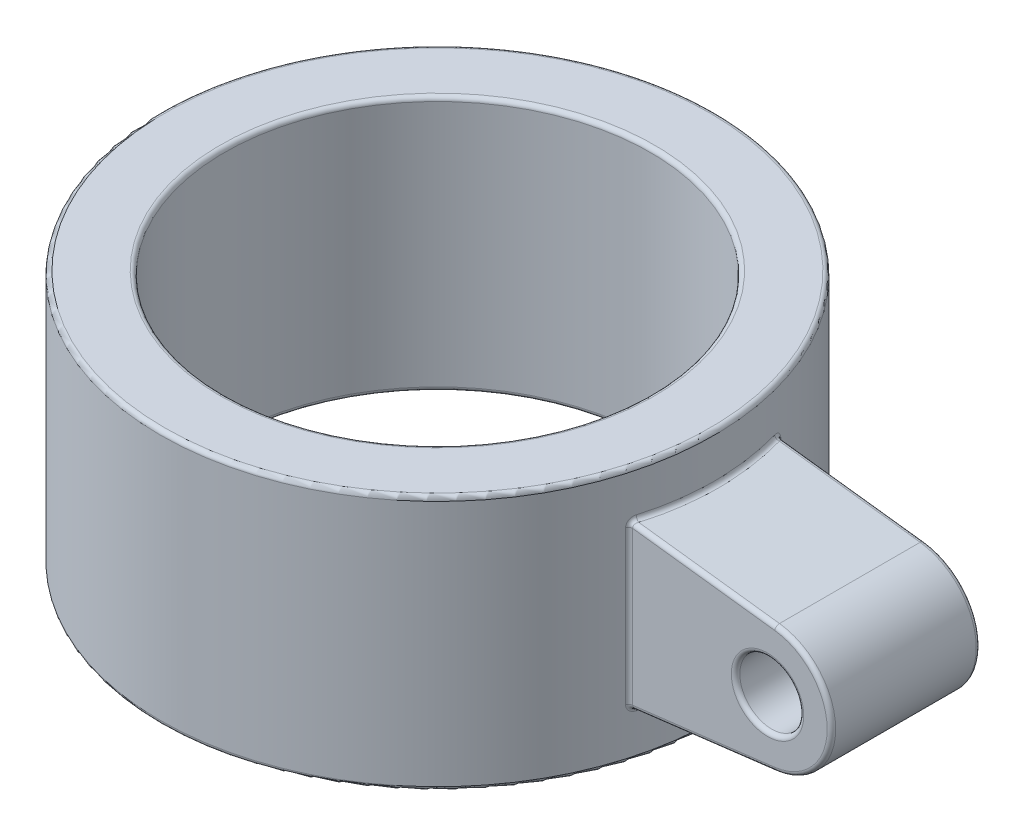
SolidWorks part; units mm, degrees
ref_plane "Front Plane" through (0, 0, 0) normal (0, 0, 1) x (1, 0, 0)
ref_plane "Top Plane" through (0, 0, 0) normal (0, 1, 0) x (1, 0, 0)
ref_plane "Right Plane" through (0, 0, 0) normal (1, 0, 0) x (0, 0, -1)
sketch "Sketch1" plane through (0, 0, 0) normal (0, 1, 0) x (1, 0, 0)
  circle A0 centre (0, 0) radius 5
  circle A1 centre (0, 0) radius 6.5
  dimension "D1" = 10
  dimension "D2" = 1.5
extrude "Boss-Extrude1" add sketch "Sketch1" along normal mid plane 6
sketch "Sketch2" plane through (0, 0, 0) normal (0, 0, 1) x (1, 0, 0)
  line L4 (5.5, 2) -> (5.5, -2)
  line L5 (5.5, -2) -> (9.682, -1.4889)
  line L6 (5.5, 2) -> (9.682, 1.4889)
  arc A0 (9.682, -1.4889) -> (9.682, 1.4889) centre (9.5, 0) ccw
  circle A1 centre (9.5, 0) radius 0.75
  point P2 (5.5, 0)
  dimension "D4" = 3
  dimension "D5" = 1.5
  dimension "D1" = 4
  dimension "D2" = 5.5
  dimension "D3" = 4
extrude "Boss-Extrude2" add sketch "Sketch2" along normal mid plane 3.5
fillet "Fillet1" radius 0.1 16 edges at (10.25, 0, -1.75) (10.25, 0, 1.75) (7.971, 1.698, -1.75) (7.971, -1.698, -1.75) (11, 0, -1.75) (7.971, 1.698, 1.75) (7.971, -1.698, 1.75) (11, 0, 1.75) (0, -3, 5) (0, 3, 5) (0, -3, 6.5) (6.5, -1.8778, 0) (6.26, 0, -1.75) (6.26, 0, 1.75) (6.5, 1.8778, 0) (0, 3, 6.5)
